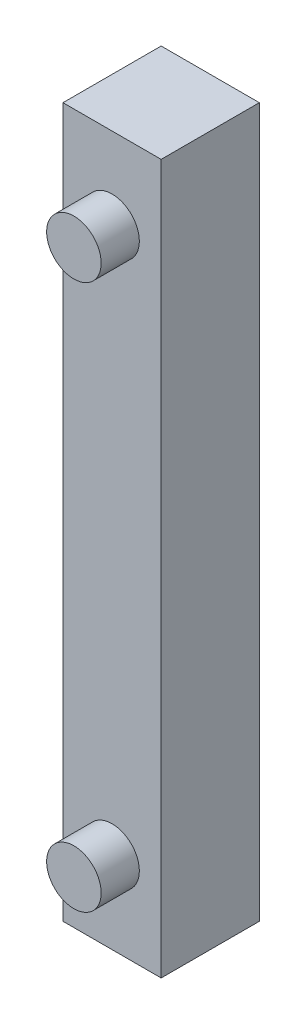
SolidWorks part; units mm, degrees
ref_plane "Front Plane" through (0, 0, 0) normal (1, 0, 0) x (0, 1, 0)
ref_plane "Top Plane" through (0, 0, 0) normal (0, 0, 1) x (0, 1, 0)
ref_plane "Right Plane" through (0, 0, 0) normal (0, 1, 0) x (-1, 0, 0)
sketch "Sketch1" plane through (0, 0, 0) normal (0, 0, 1) x (0, 1, 0)
  line L1 (-32.5, -4.5) -> (32.5, -4.5)
  line L2 (-32.5, -4.5) -> (-32.5, 4.5)
  line L3 (-32.5, 4.5) -> (32.5, 4.5)
  line L4 (32.5, -4.5) -> (32.5, 4.5)
  line L5 (-32.5, -4.5) -> (32.5, 4.5) construction
  line L6 (-32.5, 4.5) -> (32.5, -4.5) construction
  point P0 (0, 0)
  dimension "D1" = 9
  dimension "D2" = 65
extrude "Boss-Extrude1" add sketch "Sketch1" along normal mid plane 12.5
sketch "Sketch2" plane through (0, 0, 6.25) normal (0, 0, 1) x (1, 0, 0)
  circle A0 centre (0, 25) radius 2.5
  circle A1 centre (0, -25) radius 2.5
  line M3 (4.5, 32.5) -> (-4.5, 32.5)
  line M4 (-4.5, 32.5) -> (-4.5, -32.5)
  line M5 (-4.5, -32.5) -> (4.5, -32.5)
  line M6 (4.5, -32.5) -> (4.5, 32.5)
  dimension "D3" = 5
  dimension "D1" = 50
  dimension "D2" = 25
extrude "Cut-Extrude1" cut sketch "Sketch2" against normal blind 3.5 contours A1 A0 M6 M3 M4 M5
